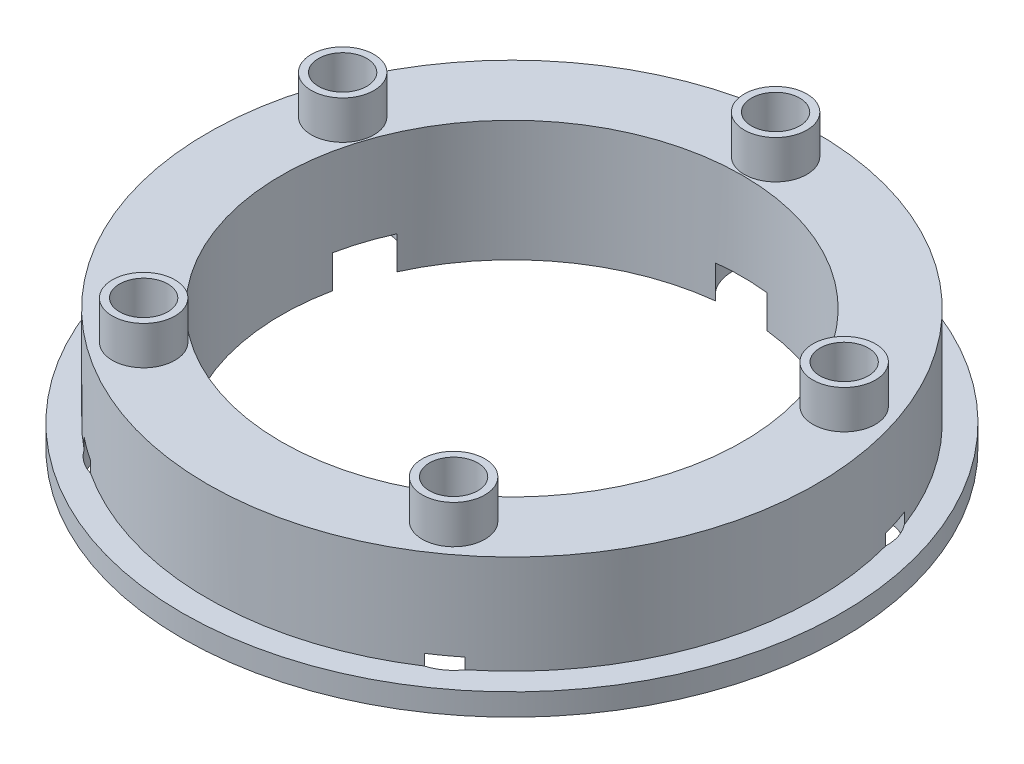
SolidWorks part; units mm, degrees
other "Markup1"
sketch "Sketch12" plane through (-30, 16, 30) normal (-0.4004, 0.8133, 0.4222) x (0.8959, 0.2506, 0.3669)
other "Markup2"
sketch "Sketch13" plane through (-30, 16, 30) normal (-0.1159, 0.8028, 0.5849) x (0.7979, -0.2754, 0.5361)
ref_plane "Front Plane" through (0, 0, 0) normal (0, 0, 1) x (1, 0, 0)
ref_plane "Top Plane" through (0, 0, 0) normal (0, 1, 0) x (1, 0, 0)
ref_plane "Right Plane" through (0, 0, 0) normal (1, 0, 0) x (0, 0, -1)
sketch "Sketch3" plane through (0, 0, 0) normal (0, 1, 0) x (1, 0, 0)
  circle A0 centre (0, 0) radius 27.7
  dimension "D1" = 55.4
extrude "Boss-Extrude2" add sketch "Sketch3" along normal blind 11
sketch "Sketch4" plane through (0, 0, 0) normal (0, 1, 0) x (1, 0, 0)
  circle A0 centre (0, 0) radius 30
  dimension "D1" = 60
extrude "Boss-Extrude3" add sketch "Sketch4" along normal blind 2
sketch "Sketch5" plane through (0, 11, 0) normal (0, 1, 0) x (1, 0, 0)
  circle A0 centre (0, 0) radius 24 construction
  circle A1 centre (0, 24) radius 2.2
  circle A2 centre (22.8254, 7.4164) radius 2.2
  circle A3 centre (14.1068, -19.4164) radius 2.2
  circle A4 centre (-14.1068, -19.4164) radius 2.2
  circle A5 centre (-22.8254, 7.4164) radius 2.2
  point P15 (0, 0)
  dimension "D1" = 48
  dimension "D2" = 4.4
  dimension "D4" = 24
  dimension "D3" = 5
extrude "Cut-Extrude1" cut sketch "Sketch5" against normal through all
sketch "Sketch9" plane through (0, 11, 0) normal (0, 1, 0) x (1, 0, 0)
  circle A0 centre (0, 0) radius 21
  dimension "D1" = 42
extrude "Cut-Extrude5" cut sketch "Sketch9" against normal through all
sketch "Sketch10" plane through (0, 11, 0) normal (0, 1, 0) x (1, 0, 0)
  circle A0 centre (-22.8254, 7.4164) radius 2.2 construction
  circle A1 centre (-22.8254, 7.4164) radius 2.2
  circle A2 centre (-22.8254, 7.4164) radius 2.85
  circle A3 centre (0, 24) radius 2.2
  circle A4 centre (0, 24) radius 2.85
  circle A5 centre (22.8254, 7.4164) radius 2.2
  circle A6 centre (22.8254, 7.4164) radius 2.85
  circle A7 centre (14.1068, -19.4164) radius 2.2
  circle A8 centre (14.1068, -19.4164) radius 2.85
  circle A9 centre (-14.1068, -19.4164) radius 2.2
  circle A10 centre (-14.1068, -19.4164) radius 2.85
  point P18 (0, 0)
  dimension "D1" = 5.7
  dimension "D2" = 5
extrude "Boss-Extrude4" add sketch "Sketch10" along normal blind 3.5
sketch "Sketch15" plane through (0, 0, 0) normal (0, -1, 0) x (1, 0, 0)
  circle A0 centre (-14.1068, 19.4164) radius 2.2 construction
  circle A1 centre (-14.1068, 19.4164) radius 2.2 construction
  circle A2 centre (-14.1068, 19.4164) radius 3.9
  circle A3 centre (14.1068, 19.4164) radius 3.9
  circle A4 centre (22.8254, -7.4164) radius 3.9
  circle A5 centre (0, -24) radius 3.9
  circle A6 centre (-22.8254, -7.4164) radius 3.9
  point P14 (0, 0)
  dimension "D1" = 7.8
  dimension "D2" = 5
extrude "Cut-Extrude6" cut sketch "Sketch15" against normal blind 3
